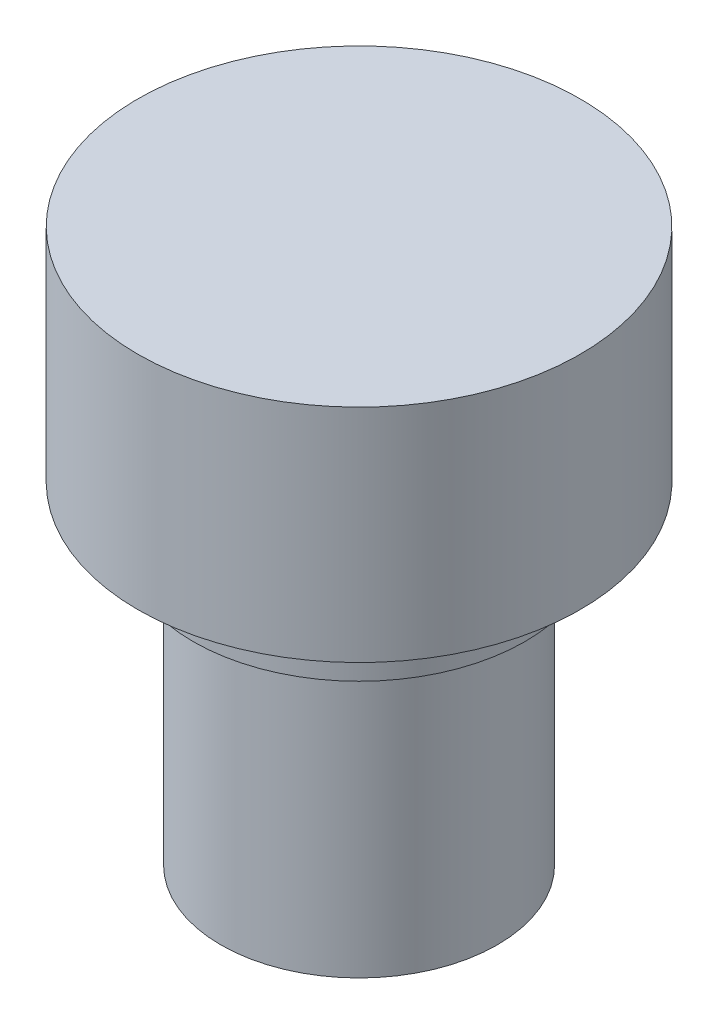
SolidWorks part; units mm, degrees
ref_plane "Plano frontal" through (0, 0, 0) normal (0, 0, 1) x (1, 0, 0)
ref_plane "Plano superior" through (0, 0, 0) normal (0, 1, 0) x (1, 0, 0)
ref_plane "Plano direito" through (0, 0, 0) normal (1, 0, 0) x (0, 0, -1)
sketch "Esboço1" plane through (0, 0, 0) normal (0, 1, 0) x (1, 0, 0)
  circle A4 centre (0, 0) radius 4
  dimension "D1" = 8
extrude "Ressalto-extrusão1" add sketch "Esboço1" along normal blind 4
sketch "Esboço4" plane through (0, 0, 0) normal (0, -1, 0) x (-1, 0, 0)
  circle A0 centre (0, 0) radius 2.5
  dimension "D1" = 5
extrude "Ressalto-extrusão2" add sketch "Esboço4" along normal blind 6
sketch "Esboço5" plane through (0, 0, 0) normal (0, -1, 0) x (1, 0, 0)
  circle A0 centre (0, 0) radius 3
  dimension "D1" = 6
extrude "Ressalto-extrusão4" add sketch "Esboço5" along normal blind 1
sketch "Esboço6" plane through (0, -6, 0) normal (0, -1, 0) x (1, 0, 0)
  point P0 (0, 0)
hole_wizard "Broca de rosquear para tarraxa de M31" positions "3DSketch1" profile "Esboço7" hole size "M3" standard "ISO"
sketch3d "3DSketch1"
  point P0 (0, 0, 0)
  point P3 (0, -6, 0)
sketch "Esboço7" plane through (0, -6, 0) normal (1, 0, 0) x (0, 0, -1)
  line L0 (0, 0) -> (0, 8.7511)
  line L1 (0, 8.7511) -> (1.25, 8)
  line L2 (1.25, 8) -> (1.25, 0)
  line L5 (1.25, 0) -> (0, 0)
  line L10 (0, 8.7511) -> (-1.25, 8) construction
  line L11 (0, -6.35) -> (0, 107.95) construction
  dimension "Hole Dia." = 2.5
  dimension "Hole Depth" = 8
  dimension "Drill Angle" = 118
